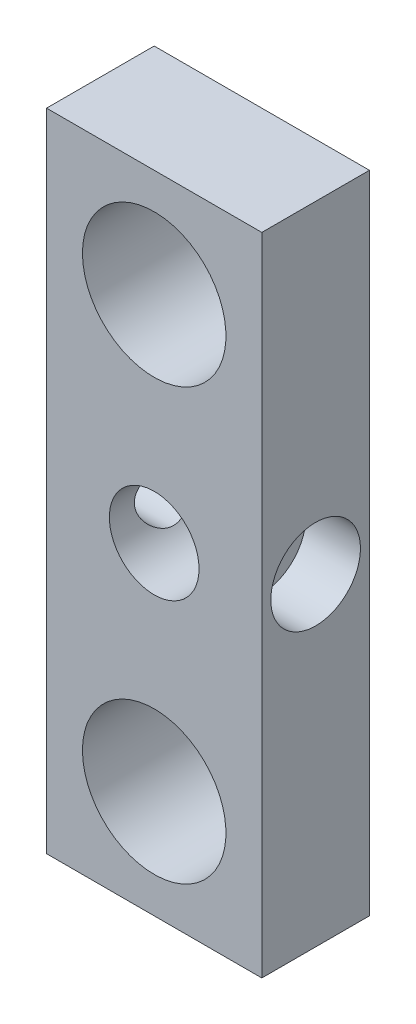
SolidWorks part; units mm, degrees
material "2024-T4"
ref_plane "Front Plane" through (0, 0, 0) normal (0, 0, 1) x (1, 0, 0)
ref_plane "Top Plane" through (0, 0, 0) normal (0, 1, 0) x (1, 0, 0)
ref_plane "Right Plane" through (0, 0, 0) normal (1, 0, 0) x (0, 0, -1)
sketch "Sketch1" plane through (0, 0, 0) normal (0, 0, 1) x (1, 0, 0)
  line L0 (0, -180.975) -> (0, -219.075) construction
  line L1 (0, -200.025) -> (-9.525, -200.025) construction
  line L2 (-9.525, -228.6) -> (9.525, -228.6)
  line L3 (-9.525, -228.6) -> (-9.525, -171.45)
  line L4 (-9.525, -171.45) -> (9.525, -171.45)
  line L5 (9.525, -228.6) -> (9.525, -171.45)
  line L6 (-9.525, -228.6) -> (9.525, -171.45) construction
  line L7 (-9.525, -171.45) -> (9.525, -228.6) construction
  circle A0 centre (0, -180.975) radius 3.175 construction
  circle A1 centre (0, -200.025) radius 3.9687
  circle A2 centre (0, -180.975) radius 6.35
  circle A3 centre (0, -219.075) radius 3.175 construction
  circle A4 centre (0, -219.075) radius 6.35
  dimension "D1" = 6.35
  dimension "D2" = 7.9375
  dimension "D3" = 19.05
  dimension "D6" = 12.7
  dimension "D4" = 19.05
  dimension "D5" = 57.15
extrude "Boss-Extrude2" add sketch "Sketch1" along normal blind 9.525
sketch "Sketch2" plane through (9.525, 0, 0) normal (1, 0, 0) x (0, 0, -1)
  line L0 (-4.7625, -228.6) -> (-4.7625, -171.45) construction
  line L1 (-9.525, -228.6) -> (0, -228.6) construction
  line L2 (-9.525, -171.45) -> (0, -171.45) construction
  point P6 (-4.7625, -200.025)
hole_wizard "CBORE for #10 Socket Head Cap Screw2" positions "Sketch8" profile "Sketch9" counterbore size "#10" standard "ANSI Inch"
sketch "Sketch8" plane through (9.525, 0, 0) normal (1, 0, 0) x (0, 0, -1)
  point P0 (-4.7625, -200.025)
sketch "Sketch9" plane through (9.525, -200.025, 4.7625) normal (0, 1, 0) x (0, 0, -1)
  line L0 (0, 0) -> (0, 20.5838)
  line L1 (0, 20.5838) -> (2.5527, 19.05)
  line L2 (2.5527, 19.05) -> (2.5527, 4.826)
  line L3 (2.5527, 4.826) -> (3.9687, 4.826)
  line L4 (3.9687, 4.826) -> (3.9688, 0)
  line L5 (3.9688, 0) -> (0, 0)
  line L10 (0, 20.5838) -> (-2.5527, 19.05) construction
  line L11 (0, -6.35) -> (0, 107.95) construction
  dimension "Hole Dia." = 5.1054
  dimension "Hole Depth" = 19.05
  dimension "C'Bore Dia." = 7.9375
  dimension "C'Bore Depth" = 4.826
  dimension "Drill Angle" = 118
